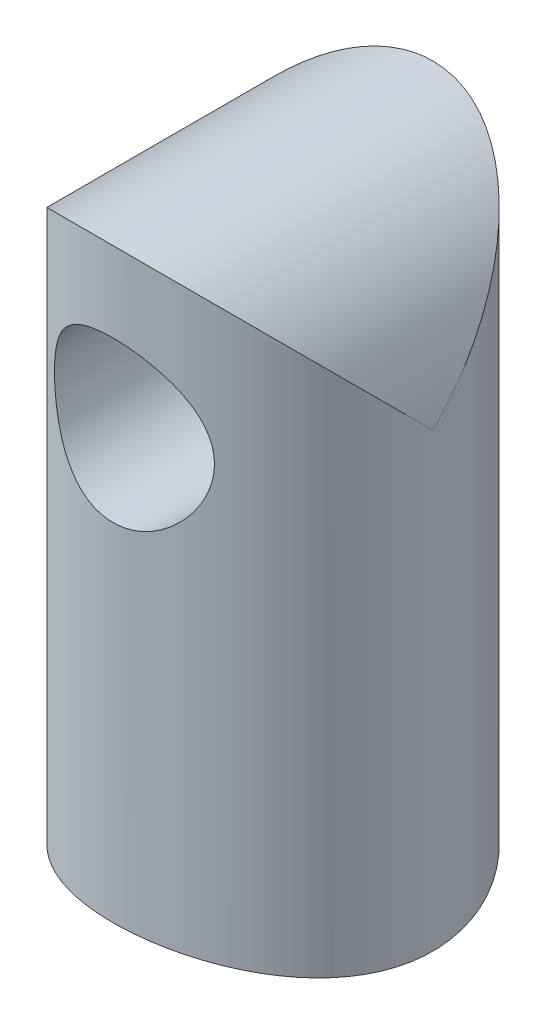
SolidWorks part; units mm, degrees
material "6061-T6 (SS)"
ref_plane "Front Plane" through (0, 0, 0) normal (0, 0, 1) x (1, 0, 0)
ref_plane "Top Plane" through (0, 0, 0) normal (0, 1, 0) x (1, 0, 0)
ref_plane "Right Plane" through (0, 0, 0) normal (1, 0, 0) x (0, 0, -1)
sketch "Sketch1" plane through (0, 0, 0) normal (0, 1, 0) x (1, 0, 0)
  circle A0 centre (0, 0) radius 9.525
  dimension "D1" = 19.05
extrude "Boss-Extrude1" add sketch "Sketch1" along normal blind 38.1
sketch "Sketch2" plane through (0, 0, 0) normal (0, 0, 1) x (1, 0, 0)
  line L0 (-9.525, 26.8624) -> (-9.525, 38.1)
  line L1 (-9.525, 38.1) -> (9.525, 38.1)
  line L2 (9.525, 38.1) -> (9.525, 26.8624)
  circle A0 centre (0, -30.2876) radius 31.75
  circle A1 centre (0, 26.8624) radius 4.7625
  arc A2 (9.525, 26.8624) -> (-9.525, 26.8624) centre (0, 26.8624) ccw
  dimension "D1" = 63.5
  dimension "D2" = 9.525
  dimension "D4" = 19.05
  dimension "D3" = 57.15
extrude "Cut-Extrude1" cut sketch "Sketch2" against normal through all and the other way through all
